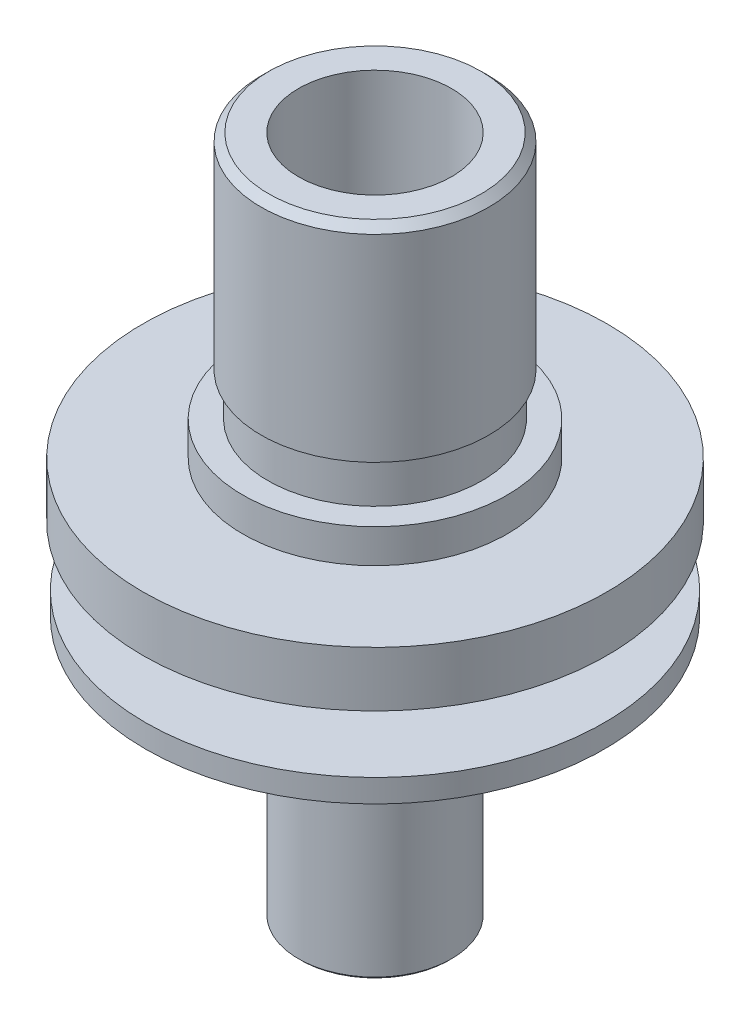
SolidWorks part; units mm, degrees
material "7075-T6 (SN)"
ref_plane "X-Y Datum" through (0, 0, 0) normal (0, 0, 1) x (1, 0, 0)
ref_plane "X-Z Datum" through (0, 0, 0) normal (0, 1, 0) x (1, 0, 0)
ref_plane "Y-Z Datum" through (0, 0, 0) normal (1, 0, 0) x (0, 0, -1)
sketch "Sketch1" plane through (0, 0, 0) normal (1, 0, 0) x (0, 0, -1)
  line L0 (0, 0) -> (-50000, 0) construction
  line L1 (0, 0) -> (0, 50000) construction
  line L2 (0, 0) -> (-25.0825, 0)
  line L3 (-25.0825, 0) -> (-25.0825, -12.319)
  line L5 (-25.0825, -17.0815) -> (-15.875, -17.0815)
  line L8 (0, -71.1505) -> (0, 0)
  line L9 (0, -71.1505) -> (-15.367, -71.1505)
  line L10 (-15.875, -17.0815) -> (-15.875, -70.6425)
  line L11 (-15.367, -71.1505) -> (-15.875, -70.6425)
  line L12 (-47.625, -12.319) -> (-47.625, -17.0815)
  line L13 (-47.625, -17.0815) -> (-25.0825, -17.0815)
  line L14 (-47.625, -12.319) -> (-25.0825, -12.319)
  dimension "D1" = 12.319
  dimension "D2" = 4.7625
  dimension "D3" = 54.069
  dimension "D4" = 47.625
  dimension "D5" = 45
  dimension "D6" = 90
  dimension "D7" = 31.75
  dimension "D8" = 0.508
  dimension "D9" = 4.7625
  dimension "D10" = 9.2075
sketch "Sketch2" plane through (0, 0, 0) normal (1, 0, 0) x (0, 0, -1)
  line L0 (0, 0) -> (-52.5, 0)
  line L1 (200000, 0) -> (-250000, 0) construction
  line L2 (-52.5, 0) -> (-52.5, 11.43)
  line L3 (-52.5, 11.43) -> (-27.4096, 11.43)
  line L4 (-27.4096, 11.43) -> (-27.4096, 18.43)
  line L5 (-27.4096, 18.43) -> (-22.225, 18.43)
  line L6 (-22.225, 18.43) -> (-22.225, 27.305)
  line L7 (-22.225, 27.305) -> (-23.6195, 27.305)
  line L10 (0, -200000) -> (0, 250000) construction
  line L11 (0, 69.85) -> (0, 0)
  line L15 (0, 69.85) -> (-22.032, 69.85)
  line L16 (-22.032, 69.85) -> (-23.6195, 68.2625)
  line L17 (-23.6195, 68.2625) -> (-23.6195, 27.305)
  line L18 (0, 0) -> (-50000, 0) construction
  line L19 (0, 0) -> (0, 50000) construction
  line L20 (0, 0) -> (0, -31242.0183) construction
  dimension "D1" = 11.43
  dimension "D2" = 58.42
  dimension "D3" = 47.2389
  dimension "D4" = 1.5875
  dimension "D5" = 45
  dimension "D6" = 54.8192
  dimension "D7" = 105
  dimension "D8" = 7
  dimension "D9" = 40.9575
  dimension "D10" = 44.45
revolve "Bearing Shaft/Flange Support" add sketch "Sketch1" angle 360 about L1
revolve "Drive Pin Support" add sketch "Sketch2" angle 360 about L19
sketch "Sketch5" plane through (0, 0, 0) normal (1, 0, 0) x (0, 0, -1)
  line L0 (0, 69.85) -> (15.875, 69.85)
  line L1 (22.032, 69.85) -> (-22.032, 69.85) construction
  line L4 (15.875, -9.525) -> (0, -9.525)
  line L5 (0, -9.525) -> (0, 69.85)
  line L6 (0, 0) -> (-50000, 0) construction
  line L7 (15.875, -9.525) -> (15.875, 69.85)
  line L8 (0, 0) -> (0, -50000) construction
  dimension "D1" = 79.375
  dimension "D4" = 31.75
revolve "Center Mass Removal" cut sketch "Sketch5" angle 360 about L8
hole_wizard "Drive Pin Holes" positions "Sketch6" profile "Sketch7" tap size "M8x1.25" standard "ANSI Metric"
sketch "Sketch6" plane through (0, 0, 0) normal (0, -1, 0) x (-1, 0, 0)
  circle A0 centre (0, 0) radius 40 construction
  point P0 (0, -40)
  dimension "D1" = 80
sketch "Sketch7" plane through (0, 0, 40) normal (1, 0, 0) x (0, 0, -1)
  line L0 (0, 0) -> (0, 69.85)
  line L1 (0, 69.85) -> (3.4, 69.85)
  line L2 (3.4, 69.85) -> (3.4, 0)
  line L5 (3.4, 0) -> (0, 0)
  line L11 (0, -6.35) -> (0, 107.95) construction
  dimension "Thru Tap Drill Dia." = 6.8
  dimension "Thru Tap Drill Depth" = 69.85
cosmetic thread "Hole Thread1" parameters "D2"=8
pattern_circular "Drive Pin Holes Pattern" count 4 over 360 about axis through (0, 0, 0) along (0, 1, 0) of "Drive Pin Holes"
cosmetic thread "Hole Thread2" parameters "D2"=8
cosmetic thread "Hole Thread3" parameters "D2"=8
cosmetic thread "Hole Thread4" parameters "D2"=8
sketch "Sketch8" plane through (0, 0, 0) normal (0, -1, 0) x (1, 0, 0)
  line L0 (0, 0) -> (-64.0279, 64.0279) construction
  line L1 (0, 0) -> (0, 72.7145) construction
  arc A0 (6.8518, 44.4362) -> (-6.8518, 44.4362) centre (0, 40) ccw
  arc A1 (6.8518, 44.4362) -> (13.2749, 35.4052) centre (113.4583, 113.4583) ccw
  arc A2 (44.4362, -6.8518) -> (44.4362, 6.8518) centre (40, 0) ccw
  arc A3 (44.4362, -6.8518) -> (44.4362, 6.8518) centre (40, 0) ccw
  arc A5 (44.4362, -6.8518) -> (35.4052, -13.2749) centre (113.4583, -113.4583) ccw
  circle A7 centre (0, 40) radius 3.4 construction
  circle A8 centre (0, 0) radius 52.5 construction
  circle A9 centre (0, 0) radius 40 construction
  arc A10 (-6.8518, -44.4362) -> (6.8518, -44.4362) centre (0, -40) ccw
  arc A11 (-6.8518, -44.4362) -> (6.8518, -44.4362) centre (0, -40) ccw
  arc A13 (-44.4362, 6.8518) -> (-44.4362, -6.8518) centre (-40, 0) ccw
  arc A14 (-44.4362, 6.8518) -> (-44.4362, -6.8518) centre (-40, 0) ccw
  arc A15 (-44.4362, 6.8518) -> (-35.4052, 13.2749) centre (-113.4583, 113.4583) ccw
  arc A16 (6.8518, 44.4362) -> (-6.8518, 44.4362) centre (0, 40) ccw
  circle A17 centre (0, 0) radius 52.5
  arc A18 (-6.8518, -44.4362) -> (-13.2749, -35.4052) centre (-113.4583, -113.4583) ccw
  arc A19 (-169.6965, 0.4112) -> (0.4112, -169.6965) centre (-113.4583, -113.4583) ccw [skipped]
  arc A20 (-13.2749, 35.4052) -> (-35.4052, 13.2749) centre (-22.4506, 22.4506) ccw
  arc A21 (-13.2749, 35.4052) -> (-6.8518, 44.4362) centre (-113.4583, 113.4583) ccw
  arc A22 (35.4052, 13.2749) -> (13.2749, 35.4052) centre (22.4506, 22.4506) ccw
  arc A23 (13.2749, -35.4052) -> (35.4052, -13.2749) centre (22.4506, -22.4506) ccw
  arc A24 (-35.4052, -13.2749) -> (-13.2749, -35.4052) centre (-22.4506, -22.4506) ccw
  arc A25 (35.4052, 13.2749) -> (44.4362, 6.8518) centre (113.4583, 113.4583) ccw
  arc A26 (13.2749, -35.4052) -> (6.8518, -44.4362) centre (113.4583, -113.4583) ccw
  arc A27 (-35.4052, -13.2749) -> (-44.4362, -6.8518) centre (-113.4583, -113.4583) ccw
  point P49 (0, 0)
  circle M10 centre (0, 0) radius 52.5
  dimension "D1" = 4.7625
  dimension "D2" = 45
  dimension "D3" = 254
  dimension "D4" = 80
  dimension "D6" = 31.75
  dimension "D7" = 31.75
  dimension "D5" = 4
  dimension "D8" = 4
extrude "Flange Support Cut" cut sketch "Sketch8" against normal up to next contours A10 A18 A13 A15 A0 A1 A2 A5 M10
sketch "Sketch10" plane through (0, -17.0815, 0) normal (0, -1, 0) x (1, 0, 0)
  line L0 (0, 0) -> (0, 50000) construction
  line L7 (0, 0) -> (50000, 0) construction
  line L8 (-5.969, -46.0335) -> (-12.2091, -46.0335)
  line L9 (5.969, -46.0375) -> (12.1938, -46.0375)
  line L10 (-42.8506, -17.8474) -> (-45.9707, -12.4434)
  line L11 (-36.8851, -28.1881) -> (-33.7727, -33.5789)
  line L12 (-36.8816, 28.186) -> (-33.7616, 33.5901)
  line L13 (-42.8541, 17.8494) -> (-45.9666, 12.4586)
  line L14 (5.969, 46.0335) -> (12.2091, 46.0335)
  line L15 (-5.969, 46.0375) -> (-12.1938, 46.0375)
  line L16 (42.8506, 17.8474) -> (45.9707, 12.4434)
  line L17 (36.8851, 28.1881) -> (33.7727, 33.5789)
  line L18 (36.8816, -28.186) -> (33.7616, -33.5901)
  line L19 (42.8541, -17.8494) -> (45.9666, -12.4586)
  arc A0 (-5.969, -46.0335) -> (5.969, -46.0375) centre (0, -46.0375) cw
  arc A1 (-42.8506, -17.8474) -> (-36.8851, -28.1881) centre (-39.8696, -23.0187) cw
  arc A3 (-36.8816, 28.186) -> (-42.8541, 17.8494) centre (-39.8696, 23.0188) cw
  circle A4 centre (0, 0) radius 47.625 construction
  arc A5 (5.969, 46.0335) -> (-5.969, 46.0375) centre (0, 46.0375) cw
  arc A6 (42.8506, 17.8474) -> (36.8851, 28.1881) centre (39.8696, 23.0187) cw
  arc A7 (36.8816, -28.186) -> (42.8541, -17.8494) centre (39.8696, -23.0188) cw
  circle A8 centre (0, 0) radius 47.625
  arc A9 (-33.7727, -33.5789) -> (-12.2091, -46.0335) centre (-24.2426, -41.9733) cw
  arc A10 (-45.9666, 12.4586) -> (-45.9707, -12.4434) centre (-48.4712, 0.008) cw
  arc A11 (-12.1938, 46.0375) -> (-33.7616, 33.5901) centre (-24.2287, 41.9813) cw
  arc A12 (33.7727, 33.5789) -> (12.2091, 46.0335) centre (24.2426, 41.9733) cw
  arc A13 (45.9666, -12.4586) -> (45.9707, 12.4434) centre (48.4712, -0.008) cw
  arc A14 (12.1938, -46.0375) -> (33.7616, -33.5901) centre (24.2287, -41.9813) cw
  point P42 (0, 0)
  point P60 (0, 0)
  dimension "D2" = 5.969
  dimension "D1" = 46.0375
  dimension "D5" = 95.25
  dimension "D6" = 12.7
  dimension "D3" = 6.2401
  dimension "D8" = 46.0375
  dimension "D4" = 6
  dimension "D7" = 6
extrude "Brake Hat Hex" cut sketch "Sketch10" along a picked direction on the side against the normal up to surface (4.7625 mm away)
sketch "Sketch11" plane through (0, -71.1505, 0) normal (0, -1, 0) x (1, 0, 0)
  circle A25 centre (0, 0) radius 9.525 construction
  circle A26 centre (0, 9.525) radius 3.175
  dimension "D1" = 19.05
  dimension "D2" = 6.35
hole_wizard "5/16 Clearnce" positions "Sketch27" profile "Sketch13" hole size "5/16" standard "ANSI Inch" end condition through all
sketch "Sketch27" plane through (0, -71.1505, 0) normal (0, -1, 0) x (-1, 0, 0)
  point P0 (0, 0)
sketch "Sketch13" plane through (0, -71.1505, 0) normal (1, 0, 0) x (0, 0, -1)
  line L0 (0, 0) -> (0, 141.0005)
  line L1 (0, 141.0005) -> (4.1021, 141.0005)
  line L2 (4.1021, 141.0005) -> (4.1021, 0)
  line L5 (4.1021, 0) -> (0, 0)
  line L11 (0, -6.35) -> (0, 107.95) construction
  dimension "Thru Hole Dia." = 8.2042
  dimension "Thru Hole Depth" = 141.0005
fillet "Hub Fillet" [suppressed] radius 0.7937
sketch "Sketch14" plane through (0, 0, 0) normal (1, 0, 0) x (0, 0, -1)
  line L0 (22.032, 69.85) -> (-22.032, 69.85) construction
  line L1 (0, 0) -> (-50000, 0) construction
  line L2 (0, 0) -> (0, -50000) construction
  circle A0 centre (0, 59.05) radius 2
  dimension "D2" = 4
  dimension "D1" = 10.8
extrude "Pin Holes" [suppressed] cut sketch "Sketch14" against normal through all
pattern_circular "Pin Hole Pattern" [suppressed] count 16 over 360
chamfer "Floral Pattern Chamfer" [suppressed] distance 3.175 angle 45
sketch3d "3DSketch2"
  line L0 (0, 0, 0) -> (0, 0, -205.74)
  line L1 (0, 0, -205.74) -> (25.4, 0, -205.74)
  line L2 (0, 0, -205.74) -> (0, -25.4, -205.74)
  dimension "D1" = 25.4
  dimension "D2" = 25.4
  dimension "D3" = 205.74
extrude "Tripod Pins" cut sketch "Sketch11" against normal blind 12.7
thread "Main Big Threads" [suppressed] pitch 2.1167 start angle 0, offset 0.3048, length 0, pitch 2.1167, diameter 47.625
ref_plane "Plane1" through (-23.8125, 70.1548, 0) normal (0, 0, 1) x (-1, 0, 0)
sketch "Thread Profile1" plane through (-23.8125, 70.1548, 0) normal (0, 0, 1) x (-1, 0, 0)
  line L0 (0, 0) -> (0, 2.1167) construction
  line L11 (0, 0) -> (0, 1.8521)
  line L12 (0, 1.8521) -> (-1.1457, 1.1906)
  line L13 (-1.1457, 1.1906) -> (-1.1457, 0.6615)
  line L15 (-1.1457, 0.6615) -> (0, 0)
  line L17 (-1.1457, 0.926) -> (0, 0.926) construction
  point P2 (0, 0)
  dimension "Pitch" = 2.1167
  dimension "Profile_Angle" = 60
  dimension "Profile_Land" = 0.5292
  dimension "Profile_Height" = 1.1457
fillet "Fillet1" radius 3.175 8 edges at (-13.2749, 5.715, 35.4052) (-35.4052, 5.715, 13.2749) (-35.4052, 5.715, -13.2749) (-13.2749, 5.715, -35.4052) (13.2749, 5.715, -35.4052) (35.4052, 5.715, -13.2749) (35.4052, 5.715, 13.2749) (13.2749, 5.715, 35.4052)
pattern_circular "CirPattern1" count 4 over 360 about axis through (0, 0, 0) along (0, 1, 0) of "Tripod Pins"
sketch "Sketch28" plane through (0, 11.43, 0) normal (0, 1, 0) x (1, 0, 0)
  circle A0 centre (0, 0) radius 48.1625
extrude "Boss-Extrude1" add sketch "Sketch28" against normal up to surface (11.43 mm away) up to face at (0, 0, -43.4)
sketch "Sketch29" plane through (0, -12.319, 0) normal (0, 1, 0) x (1, 0, 0)
  circle A0 centre (0, 0) radius 47.625
extrude "Boss-Extrude2" add sketch "Sketch29" against normal up to surface (4.7625 mm away)
sketch "Sketch30" plane through (0, 0, 0) normal (0, 0, 1) x (1, 0, 0)
  line L0 (-47.625, -17.0815) -> (-47.625, -4.3815)
  line L1 (-47.625, -17.0815) -> (-15.875, -17.0815)
  line L2 (-15.875, -17.0815) -> (-15.875, -70.6425)
  line L3 (15.875, -70.6425) -> (-15.875, -70.6425) construction
  line L4 (-15.875, -17.0815) -> (-15.875, -70.6425) construction
  line L5 (-15.875, -70.6425) -> (-15.367, -71.1505)
  line L6 (-48.1625, 11.43) -> (-48.1625, 20.955)
  line L7 (-47.625, -4.3815) -> (-48.1625, -4.3815)
  line L8 (-48.1625, -4.3815) -> (-48.1625, 11.43)
  line L9 (-47.625, -12.319) -> (-47.625, -17.0815) construction
  dimension "D1" = 9.525
  dimension "D2" = 12.7
sketch "Sketch31" plane through (0, 0, 0) normal (0, 0, 1) x (1, 0, 0)
  line L0 (-23.7172, 69.85) -> (23.7172, 69.85) construction
  line L1 (0, 0) -> (0, 50000) construction
  line L2 (22.032, 69.85) -> (-22.032, 69.85) construction
  line L3 (23.7173, 68.0275) -> (23.7173, 27.305)
  line L5 (22.225, 18.43) -> (27.4096, 18.43)
  line L6 (27.4096, 18.43) -> (27.4096, 11.43)
  line L7 (27.4096, 11.43) -> (48.1625, 11.43)
  line L8 (22.225, 18.43) -> (22.225, 27.305) construction
  line L9 (22.225, 18.43) -> (22.225, 25.8127)
  line L10 (22.225, 18.43) -> (27.4096, 18.43)
  line L11 (22.225, 27.305) -> (23.7173, 27.305) construction
  line L12 (23.7173, 27.305) -> (22.225, 25.8127)
  line L13 (23.7173, 68.0275) -> (21.8948, 69.85)
  line L15 (-22.225, 27.305) -> (22.225, 27.305) construction
  point P5 (0, 69.85)
  point P11 (0, 0)
  point P19 (0, 0)
  dimension "D1" = 47.4345
  dimension "D2" = 45
  dimension "D3" = 45
  dimension "D4" = 21.8948
  dimension "D5" = 23.7173
